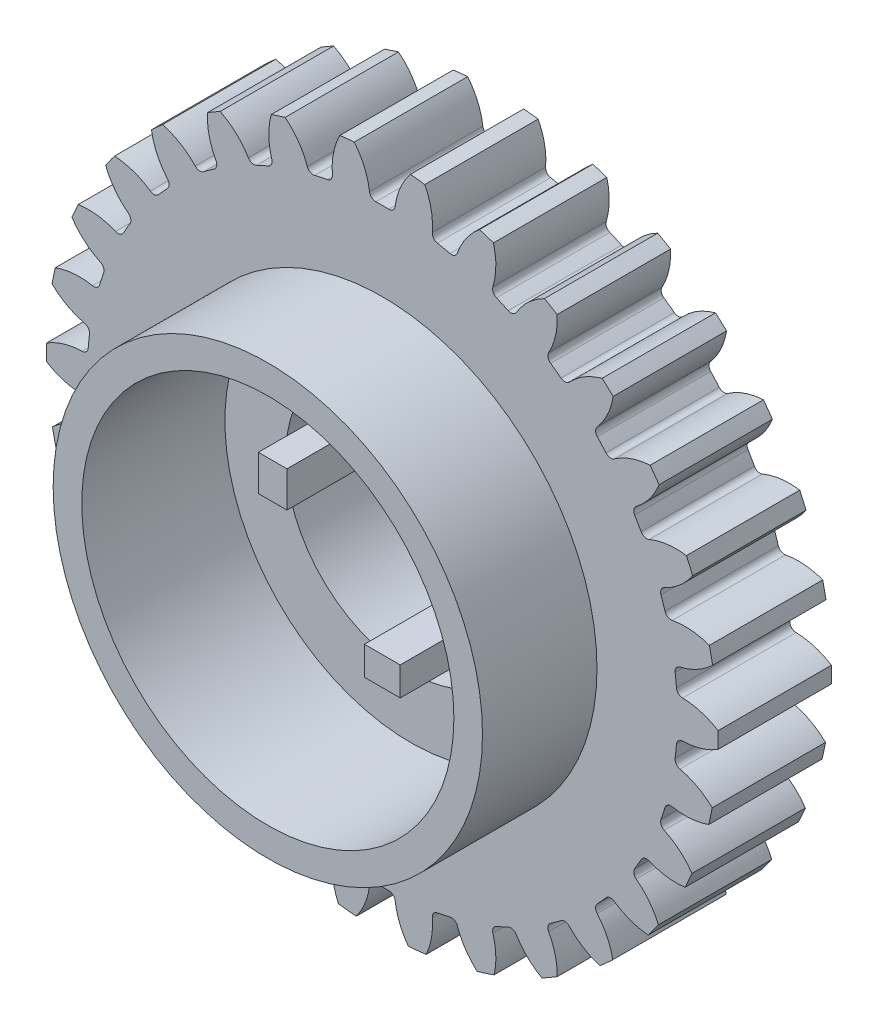
SolidWorks part; units mm, degrees
ref_plane "Front Plane" through (0, 0, 0) normal (0, 0, 1) x (1, 0, 0)
ref_plane "Top Plane" through (0, 0, 0) normal (0, 1, 0) x (1, 0, 0)
ref_plane "Right Plane" through (0, 0, 0) normal (1, 0, 0) x (0, 0, -1)
sketch "Sketch1" plane through (0, 0, 0) normal (0, 0, 1) x (1, 0, 0)
  circle A0 centre (0, 0) radius 25
  circle A1 centre (0, 0) radius 23.33
  circle A2 centre (0, 0) radius 26.665
  dimension "D1" = 50
  dimension "D2" = 53.33
  dimension "D3" = 46.66
extrude "Boss-Extrude1" add sketch "Sketch1" along normal mid plane 9 contours A2
sketch "Sketch2" plane through (0, 0, 0) normal (0, 0, 1) x (1, 0, 0)
  line L0 (0, 0) -> (0, 26.665) construction
  line L1 (-1.3084, 24.9657) -> (1.3084, 24.9657) construction
  line L2 (0, 21.3709) -> (-2.2573, 27.5728) construction
  line L3 (0, 0) -> (-0.9803, 23.3094) construction
  line L4 (0, 0) -> (2.7873, 26.5189) construction
  line L5 (1.3084, 24.9657) -> (3.9109, 24.6922) construction
  circle A0 centre (0, 0) radius 23.33 construction
  arc A1 (0.9803, 23.3094) -> (-0.9803, 23.3094) centre (0, 0) ccw
  circle A2 centre (0, 0) radius 26.665 construction
  arc A3 (-0.9803, 23.3094) -> (-3.1688, 27.4829) centre (-6.4966, 23.0774) ccw
  arc A4 (0.9803, 23.3094) -> (3.1688, 27.4829) centre (6.4966, 23.0774) cw
  circle A6 centre (0, 0) radius 25 construction
  circle A7 centre (0, 0) radius 27.665
  arc A8 (3.1688, 27.4829) -> (-3.1688, 27.4829) centre (0, 0) ccw
  dimension "D2" = 20
  dimension "D3" = 6
  dimension "D1" = 1
extrude "Cut-Extrude1" cut sketch "Sketch2" against normal mid plane 16.67
fillet "Fillet1" radius 0.5 2 edges at (0.9803, 23.3094, 0) (-0.9803, 23.3094, 0)
pattern_circular "CirPattern1" count 30 over 360 about axis through (0, -0.1053, 0) along (0, 0, 1) of "Cut-Extrude1", "Fillet1"
sketch "Sketch3" plane through (0, 0, 4.5) normal (0, 0, 1) x (1, 0, 0)
  circle A0 centre (0, 0) radius 8.75
  dimension "D1" = 17.5
scale "Scale1" bodies to scale 104 scale about centroid uniform scaling yes scale factor 0.88
extrude "Cut-Extrude2" cut sketch "Sketch3" against normal mid plane 50
sketch "Sketch4" plane through (0, 0, 3.96) normal (0, 0, 1) x (1, 0, 0)
  line L0 (-8.6603, -1.25) -> (-8.6603, 1.25)
  line L6 (-8.6603, 1.25) -> (-6.6603, 1.25)
  line L11 (-1.25, -8.6603) -> (-1.25, -6.6603)
  line L12 (-1.25, -6.6603) -> (1.25, -6.6603)
  line L13 (-1.25, 8.6603) -> (1.25, 8.6603)
  line L14 (8.6603, -1.25) -> (8.6603, 1.25)
  line L15 (-1.25, -8.6603) -> (1.25, -8.6603)
  line L17 (8.6603, 1.25) -> (6.6603, 1.25)
  line L18 (6.6603, 1.25) -> (6.6603, -1.25)
  line L20 (-1.25, 8.6603) -> (-1.25, 6.6603)
  line L22 (-1.25, 6.6603) -> (1.25, 6.6603)
  line L23 (1.25, 6.6603) -> (1.25, 8.6603)
  line L24 (-6.6603, 1.25) -> (-6.6603, -1.25)
  line L25 (-6.6603, -1.25) -> (-8.6603, -1.25)
  line L26 (6.6603, -1.25) -> (8.6603, -1.25)
  line L27 (1.25, -6.6603) -> (1.25, -8.6603)
  circle A0 centre (0, 0) radius 8.75 construction
  point P0 (0, 0)
  point P6 (0, 0)
  dimension "D2" = 2
  dimension "D4" = 2
  dimension "D5" = 2
  dimension "D6" = 2
sketch "Sketch5" plane through (0, 0, 0) normal (0, 0, 1) x (1, 0, 0)
  circle A1 centre (0, 0) radius 15
  dimension "D1" = 30
extrude "Boss-Extrude3" add sketch "Sketch5" along normal blind 8 from surface at 3.96 starting at face at (8.75, 0, 3.96)
sketch "Sketch6" plane through (0, 0, 11.96) normal (0, 0, 1) x (1, 0, 0)
  circle A0 centre (0, 0) radius 13
  dimension "D1" = 26
extrude "Cut-Extrude4" cut sketch "Sketch6" against normal blind 10
extrude "Boss-Extrude4" add sketch "Sketch4" against normal blind 8 separate body
equation "\"M\"= 1.6666'modül"
equation "\"z\"= 30'dişli sayısı"
equation "\"b\"= \"M\" * 10'dlşli genişliği"
equation "\"d0\"= \"M\" * \"z\"'bölüm daire çapı"
equation "\"da\"= \"M\" * ( \"z\" + 2 )'DİŞ ÜST ÇAPI"
equation "\"df\"= \"M\" * ( \"z\" - 2 )'diş dipi çapı"
equation "\"r\"= \"M\" * 0.3'neyse"
equation "\"q\"= 20deg'kuvvet açısı"
equation "\"y\"= 180 / 30'tasarım açısı"
